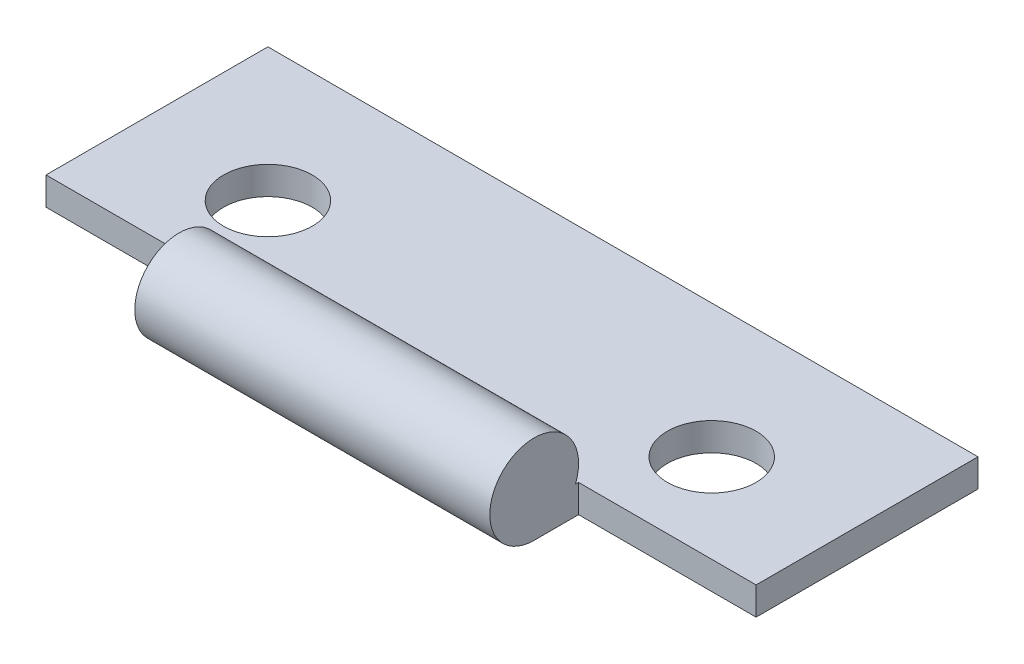
SolidWorks part; units mm, degrees
material "Bronce al estaño"
ref_plane "Front Plane" through (0, 0, 0) normal (0, 0, 1) x (1, 0, 0)
ref_plane "Top Plane" through (0, 0, 0) normal (0, 1, 0) x (1, 0, 0)
ref_plane "Right Plane" through (0, 0, 0) normal (1, 0, 0) x (0, 0, -1)
sketch "Sketch1" plane through (0, 0, 0) normal (0, 1, 0) x (1, 0, 0)
  line L0 (12.7, 9.525) -> (12.7, 0) construction
  line L1 (25.4, 9.525) -> (25.4, 1.5875)
  line L2 (0, 9.525) -> (0, 1.5875)
  line L3 (0, 9.525) -> (25.4, 9.525)
  line L4 (25.4, 1.5875) -> (19.05, 1.5875)
  line L5 (0, 1.5875) -> (6.35, 1.5875)
  line L6 (6.35, 1.5875) -> (6.35, 0)
  line L7 (6.35, 0) -> (19.05, 0)
  line L8 (19.05, 1.5875) -> (19.05, 0)
  circle A0 centre (4.7625, 4.7625) radius 1.5875
  circle A1 centre (20.6375, 4.7625) radius 1.5875
  dimension "D3" = 3.175
  dimension "D1" = 7.9375
  dimension "D2" = 25.4
  dimension "D4" = 6.35
  dimension "D5" = 1.5875
extrude "Boss-Extrude1" add sketch "Sketch1" along normal blind 1
sketch "Sketch2" plane through (6.35, 0, 0) normal (-1, 0, 0) x (0, 0, 1)
  circle A0 centre (0, 1.5875) radius 1.5875
  point P0 (0, 0)
  dimension "D2" = 1.5875
extrude "Boss-Extrude2" add sketch "Sketch2" against normal blind 12.7
